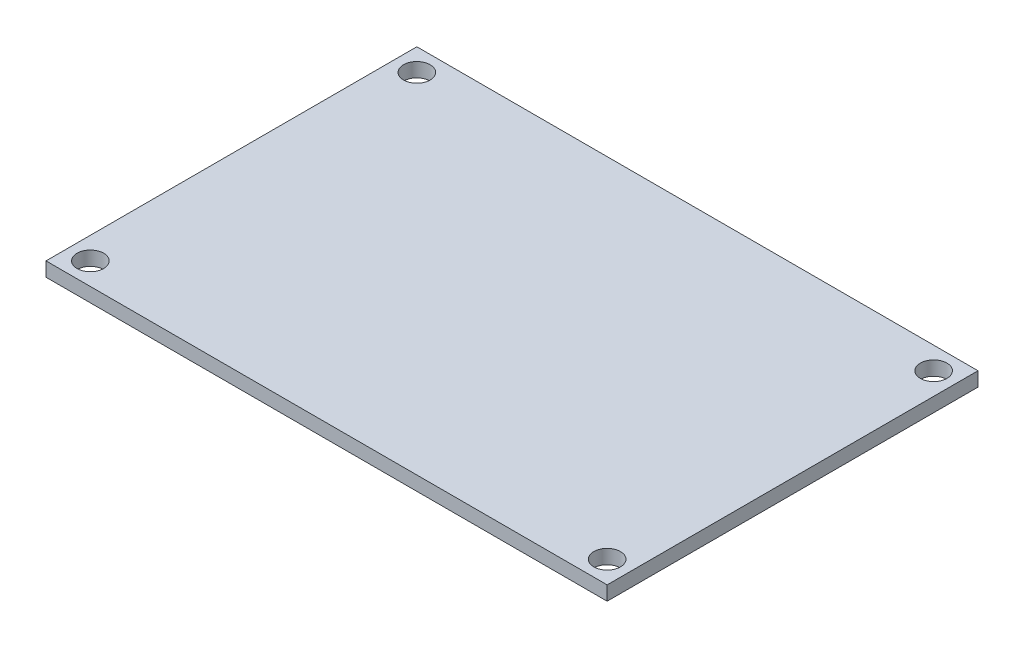
SolidWorks part; units mm, degrees
ref_plane "Front Plane" through (0, 0, 0) normal (0, 0, 1) x (1, 0, 0)
ref_plane "Top Plane" through (0, 0, 0) normal (0, 1, 0) x (1, 0, 0)
ref_plane "Right Plane" through (0, 0, 0) normal (1, 0, 0) x (0, 0, -1)
sketch "Sketch1" plane through (0, 0, 0) normal (0, 1, 0) x (1, 0, 0)
  line L0 (0, -55) -> (0, 55) construction
  line L1 (-31.625, -20.9) -> (31.625, -20.9)
  line L2 (-31.625, -20.9) -> (-31.625, 20.9)
  line L3 (-31.625, 20.9) -> (31.625, 20.9)
  line L4 (31.625, -20.9) -> (31.625, 20.9)
  line L5 (-31.625, -20.9) -> (31.625, 20.9) construction
  line L6 (-31.625, 20.9) -> (31.625, -20.9) construction
  line L7 (-55, 0) -> (55, 0) construction
  circle A0 centre (-29.125, 18.4) radius 1.5
  circle A1 centre (29.125, 18.4) radius 1.5
  circle A2 centre (29.125, -18.4) radius 1.5
  circle A3 centre (-29.125, -18.4) radius 1.5
  point P0 (0, 0)
  dimension "D3" = 3
  dimension "D1" = 41.8
  dimension "D2" = 63.25
  dimension "D4" = 2.5
  dimension "D5" = 2.5
extrude "Boss-Extrude1" add sketch "Sketch1" along normal blind 1.6
